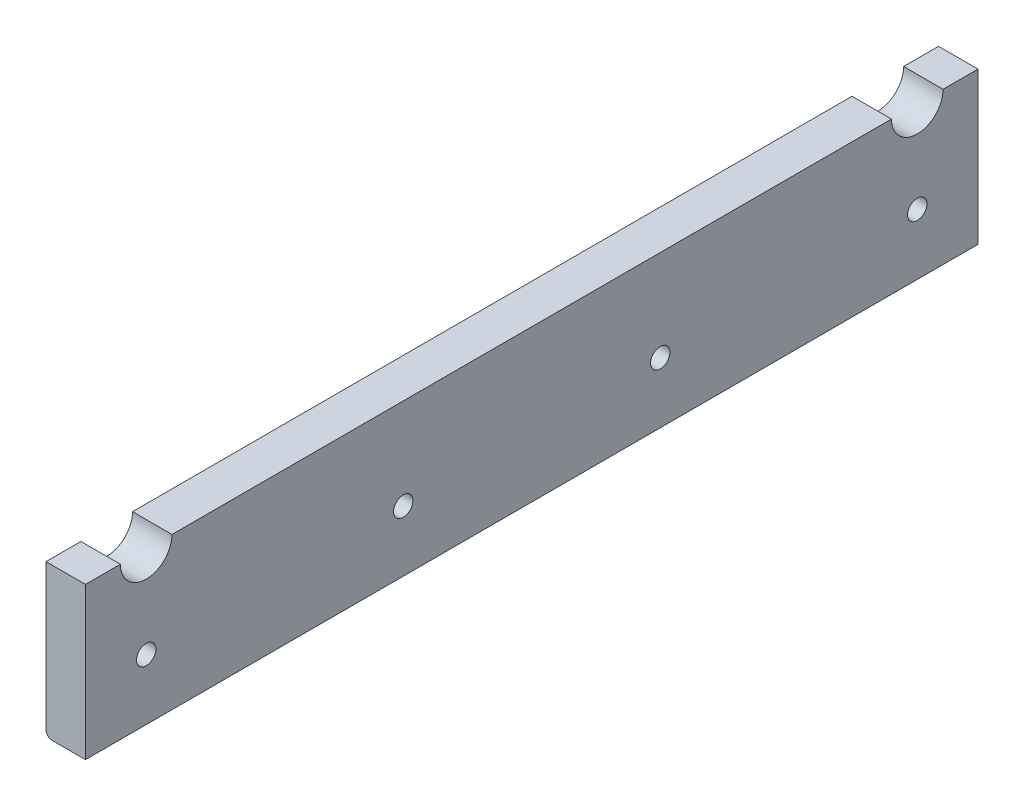
SolidWorks part; units mm, degrees
ref_plane "前视基准面" through (0, 0, 0) normal (0, 0, 1) x (1, 0, 0)
ref_plane "上视基准面" through (0, 0, 0) normal (0, 1, 0) x (1, 0, 0)
ref_plane "右视基准面" through (0, 0, 0) normal (1, 0, 0) x (0, 0, -1)
sketch "草图2" plane through (0, 0, 0) normal (0, 0, 1) x (1, 0, 0)
  line L1 (3.25, 12.5) -> (-3.25, 12.5)
  line L2 (3.25, 12.5) -> (3.25, -12.5)
  line L3 (3.25, -12.5) -> (-3.25, -12.5)
  line L4 (-3.25, 12.5) -> (-3.25, -12.5)
  line L5 (3.25, 12.5) -> (-3.25, -12.5) construction
  line L6 (3.25, -12.5) -> (-3.25, 12.5) construction
  point P0 (0, 0)
  dimension "D1" = 6.5
  dimension "D2" = 25
extrude "凸台-拉伸1" add sketch "草图2" along normal mid plane 147
fillet "圆角1" radius 1 1 edges at (-3.25, -12.5, 0)
sketch "草图3" plane through (-3.25, 0, 0) normal (-1, 0, 0) x (0, 0, 1)
  line L0 (63.5, -2.5) -> (21.1667, -2.5) construction
  line L1 (21.1667, -2.5) -> (-21.1667, -2.5) construction
  line L2 (-21.1667, -2.5) -> (-63.5, -2.5) construction
  line L3 (73.5, 12.5) -> (73.5, -11.5) construction
  line L4 (73.5, -12.5) -> (-73.5, -12.5) construction
  line L5 (-73.5, 12.5) -> (-73.5, -11.5) construction
  circle A0 centre (63.5, -2.5) radius 1.6
  circle A1 centre (21.1667, -2.5) radius 1.6
  circle A2 centre (-21.1667, -2.5) radius 1.6
  circle A3 centre (-63.5, -2.5) radius 1.6
  dimension "D1" = 10
  dimension "D2" = 10
  dimension "D3" = 10
  dimension "D4" = 3.2
extrude "切除-拉伸1" cut sketch "草图3" against normal through all
chamfer "倒角2" distance 2 angle 45 4 edges at (-3.25, -4.1, -63.5) (-3.25, -4.1, -21.1667) (-3.25, -4.1, 21.1667) (-3.25, -4.1, 63.5)
sketch "草图4" plane through (-3.25, 0, 0) normal (-1, 0, 0) x (0, 0, 1)
  line L0 (73.5, 12.5) -> (-73.5, 12.5) construction
  line L1 (-63.5, 12.5) -> (-63.5, -2.5) construction
  line L2 (63.5, 12.5) -> (63.5, -2.5) construction
  circle A0 centre (-63.5, 12.5) radius 4.25
  circle A1 centre (63.5, 12.5) radius 4.25
  dimension "D1" = 8.5
extrude "切除-拉伸2" cut sketch "草图4" against normal through all
